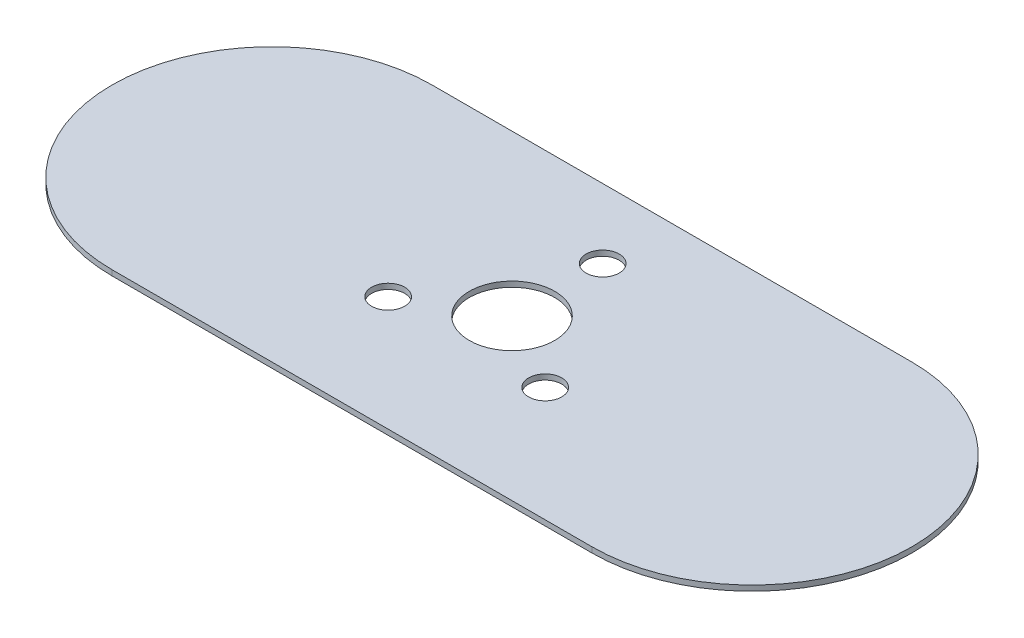
SolidWorks part; units mm, degrees
ref_plane "Front Plane" through (0, 0, 0) normal (0, 0, 1) x (1, 0, 0)
ref_plane "Top Plane" through (0, 0, 0) normal (0, 1, 0) x (1, 0, 0)
ref_plane "Right Plane" through (0, 0, 0) normal (1, 0, 0) x (0, 0, -1)
sketch "Sketch1" plane through (0, 0, 0) normal (0, 1, 0) x (1, 0, 0)
  line L0 (-22.5, 0) -> (22.5, 0) construction
  line L1 (-22.5, 15) -> (22.5, 15)
  line L2 (-22.5, -15) -> (22.5, -15)
  arc A0 (-22.5, 15) -> (-22.5, -15) centre (-22.5, 0) ccw
  arc A1 (22.5, -15) -> (22.5, 15) centre (22.5, 0) ccw
  point P2 (0, 0)
  dimension "D1" = 30
  dimension "D2" = 45
extrude "Boss-Extrude1" add sketch "Sketch1" along normal blind 0.508 contours A0 L2 A1 L1
sketch "Sketch2" plane through (0, 0.508, 0) normal (0, 1, 0) x (1, 0, 0)
  circle A0 centre (0, 0) radius 8.5 construction
  circle A1 centre (0, 8.5) radius 1.55
  circle A2 centre (7.3612, -4.25) radius 1.55
  circle A3 centre (-7.3612, -4.25) radius 1.55
  circle A4 centre (0, 0) radius 4
  point P11 (0, 0)
  dimension "D1" = 17
  dimension "D2" = 3.1
  dimension "D4" = 8
  dimension "D3" = 3
extrude "Cut-Extrude1" cut sketch "Sketch2" against normal blind 1.6
